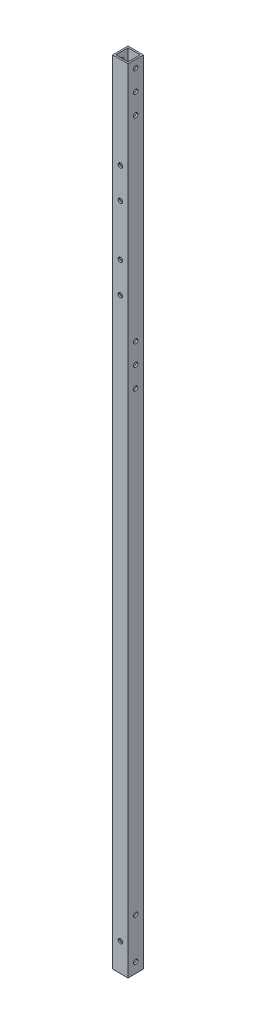
SolidWorks part; units mm, degrees
material "5052-H34"
ref_plane "正面" through (0, 0, 0) normal (0, 0, 1) x (1, 0, 0)
ref_plane "平面" through (0, 0, 0) normal (0, 1, 0) x (1, 0, 0)
ref_plane "右側面" through (0, 0, 0) normal (1, 0, 0) x (0, 0, -1)
sketch "ｽｹｯﾁ1" plane through (0, 0, 0) normal (0, 1, 0) x (1, 0, 0)
  line L1 (0, 0) -> (15, 0)
  line L2 (0, 0) -> (0, 15)
  line L3 (0, 15) -> (15, 15)
  line L4 (15, 0) -> (15, 15)
  dimension "D1" = 15
  dimension "D2" = 15
extrude "押し出し-薄板1" add sketch "ｽｹｯﾁ1" along normal blind 775 thin thin type one direction reverse wall 1.5
sketch "ｽｹｯﾁ2" plane through (15, 0, 0) normal (1, 0, 0) x (0, 0, -1)
  line L0 (7.5, 775) -> (7.5, 0) construction
  line L1 (0, 775) -> (15, 775) construction
  line L2 (0, 0) -> (15, 0) construction
  line L3 (0, 775) -> (0, 0) construction
  line L4 (7.5, 516) -> (15, 516) construction
  line L5 (15, 775) -> (15, 0) construction
  circle A3 centre (7.5, 10) radius 2.15
  circle A8 centre (7.5, 516) radius 2.15
  circle A10 centre (7.5, 767.5) radius 2.15
  circle A11 centre (7.5, 50) radius 2.15
  circle A12 centre (7.5, 536) radius 2.15
  circle A14 centre (7.5, 496) radius 2.15
  circle A15 centre (7.5, 747.5) radius 2.15
  circle A16 centre (7.5, 727.5) radius 2.15
  dimension "D2" = 7.5
  dimension "D3" = 4.3
  dimension "D4" = 7.5
  dimension "D5" = 10
  dimension "D6" = 4.3
  dimension "D7" = 7.5
  dimension "D8" = 40
  dimension "D9" = 40
  dimension "D10" = 20
  dimension "D11" = 20
  dimension "D12" = 7.5
  dimension "D13" = 516
extrude "ｶｯﾄ - 押し出し1" cut sketch "ｽｹｯﾁ2" against normal up to surface (15 mm away) up to face at (0, 387.5, -7.5)
sketch "ｽｹｯﾁ3" plane through (0, 0, 0) normal (0, 0, 1) x (1, 0, 0)
  line L0 (7.5, 775) -> (7.5, 0) construction
  line L1 (0, 775) -> (15, 775) construction
  line L2 (0, 0) -> (15, 0) construction
  circle A0 centre (7.5, 685) radius 2.15
  circle A1 centre (7.5, 655) radius 2.15
  circle A2 centre (7.5, 605) radius 2.15
  circle A3 centre (7.5, 575) radius 2.15
  circle A4 centre (7.5, 27.5) radius 2.15
  dimension "D1" = 4.3
  dimension "D2" = 30
  dimension "D3" = 575
  dimension "D4" = 30
  dimension "D5" = 50
  dimension "D6" = 4.3
  dimension "D7" = 27.5
extrude "ｶｯﾄ - 押し出し2" cut sketch "ｽｹｯﾁ3" against normal up to surface (15 mm away) up to face at (7.5, 387.5, -15)
